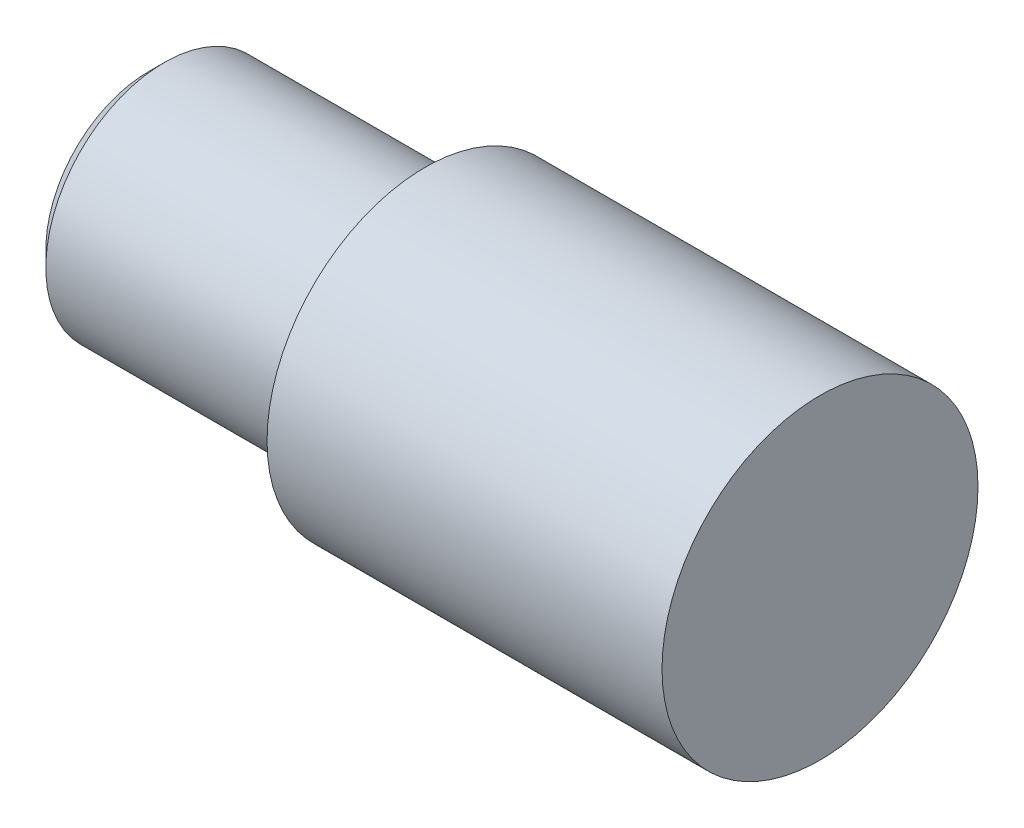
SolidWorks part; units mm, degrees
ref_plane "Front Plane" through (0, 0, 0) normal (0, 0, 1) x (1, 0, 0)
ref_plane "Top Plane" through (0, 0, 0) normal (0, 1, 0) x (1, 0, 0)
ref_plane "Right Plane" through (0, 0, 0) normal (1, 0, 0) x (0, 0, -1)
sketch "Sketch1" plane through (0, 0, 0) normal (1, 0, 0) x (0, 0, -1)
  circle A0 centre (0, 0) radius 2
  dimension "D1" = 4
extrude "Boss-Extrude1" add sketch "Sketch1" along normal blind 5
sketch "Sketch2" plane through (0, 0, 0) normal (-1, 0, 0) x (0, 0, 1)
  circle A0 centre (0, 0) radius 1.5
  dimension "D1" = 3
extrude "Boss-Extrude2" add sketch "Sketch2" along normal blind 3.5 contours A0
cosmetic thread "Cosmetic Thread1" parameters "D2"=2.439
chamfer "Chamfer1" distance 0.2 angle 45 1 edges at (-3.5, 0, 1.5)
